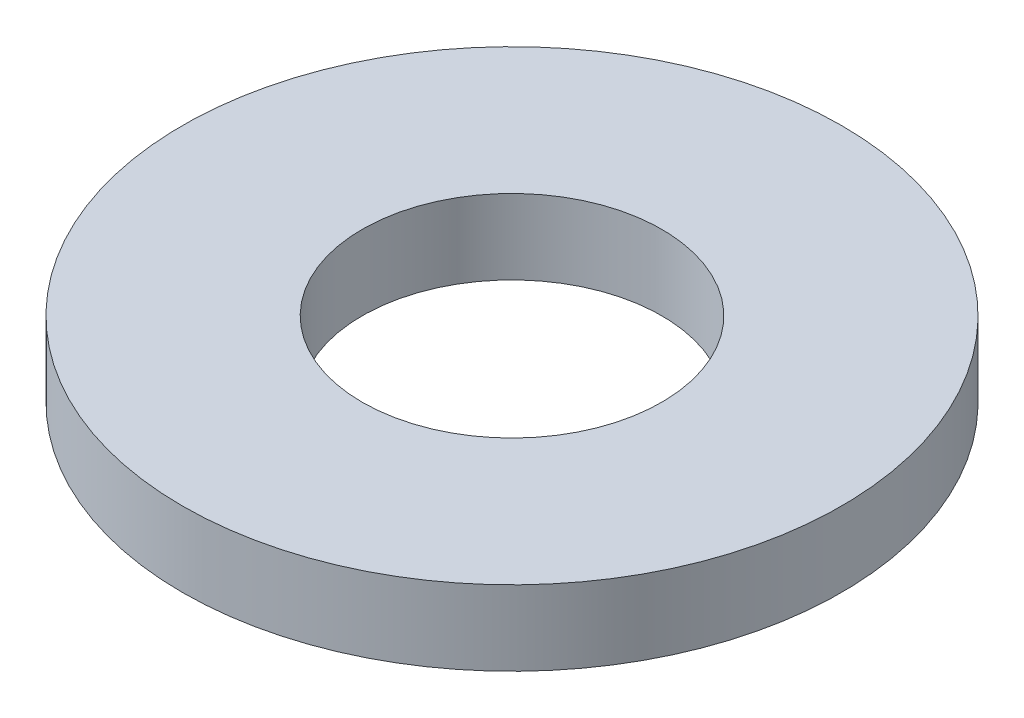
SolidWorks part; units mm, degrees
ref_plane "Спереди" through (0, 0, 0) normal (0, 0, 1) x (1, 0, 0)
ref_plane "Сверху" through (0, 0, 0) normal (0, 1, 0) x (1, 0, 0)
ref_plane "Справа" through (0, 0, 0) normal (1, 0, 0) x (0, 0, -1)
sketch "Эскиз1" plane through (0, 0, 0) normal (0, 1, 0) x (1, 0, 0)
  circle A0 centre (0, 0) radius 10
  circle A1 centre (0, 0) radius 22
extrude "Вытянуть1" add sketch "Эскиз1" along normal blind 5
